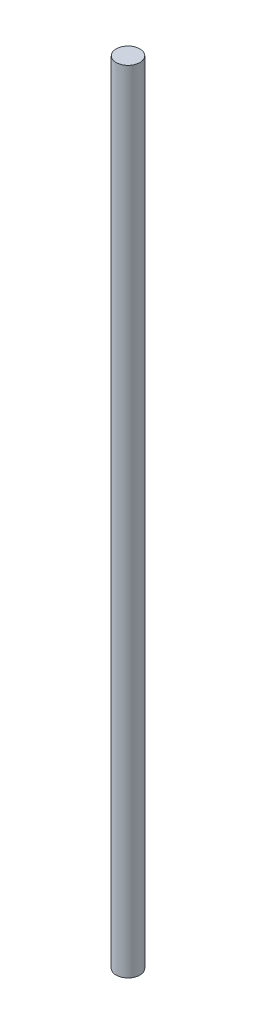
SolidWorks part; units mm, degrees
material "1060 Alloy"
ref_plane "Front Plane" through (0, 0, 0) normal (0, 0, 1) x (1, 0, 0)
ref_plane "Top Plane" through (0, 0, 0) normal (0, 1, 0) x (1, 0, 0)
ref_plane "Right Plane" through (0, 0, 0) normal (1, 0, 0) x (0, 0, -1)
sketch "Sketch2" plane through (0, 0, 0) normal (0, 1, 0) x (1, 0, 0)
  circle A0 centre (0, 0) radius 1.5
  dimension "D1" = 3
extrude "Boss-Extrude1" add sketch "Sketch2" along normal blind 100
